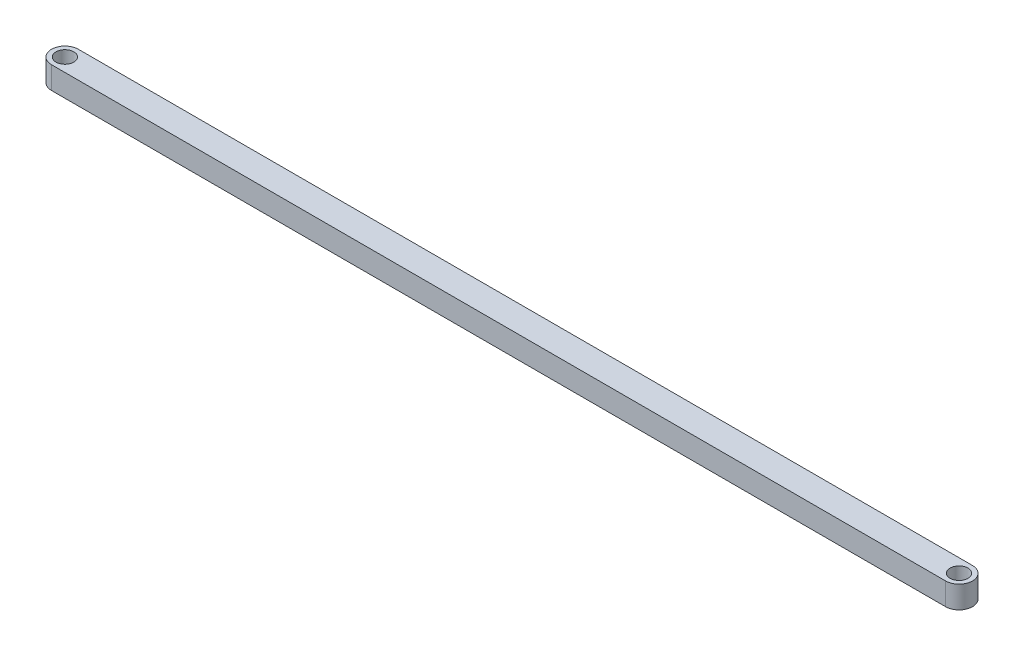
SolidWorks part; units mm, degrees
ref_plane "Front Plane" through (0, 0, 0) normal (0, 0, 1) x (1, 0, 0)
ref_plane "Top Plane" through (0, 0, 0) normal (0, 1, 0) x (1, 0, 0)
ref_plane "Right Plane" through (0, 0, 0) normal (1, 0, 0) x (0, 0, -1)
sketch "Sketch1" plane through (0, 0, 0) normal (0, 1, 0) x (1, 0, 0)
  line L1 (-50, -1.5) -> (50, -1.5)
  line L2 (-50, -1.5) -> (-50, 1.5)
  line L3 (-50, 1.5) -> (50, 1.5)
  line L4 (50, -1.5) -> (50, 1.5)
  line L5 (-50, -1.5) -> (50, 1.5) construction
  line L6 (-50, 1.5) -> (50, -1.5) construction
  circle A0 centre (-50, 0) radius 1.5
  circle A1 centre (50, 0) radius 1.5
  circle A2 centre (-50, 0) radius 1
  circle A3 centre (50, 0) radius 1
  point P0 (0, 0)
  dimension "D1" = 2
  dimension "D2" = 0.5
  dimension "D3" = 100
extrude "Boss-Extrude1" add sketch "Sketch1" along normal blind 2.5 contours A2 L2 A0 | A2 L2 A0 | A1 L3 A0 L1 | A3 L4 A1 | A3 L4 A1
